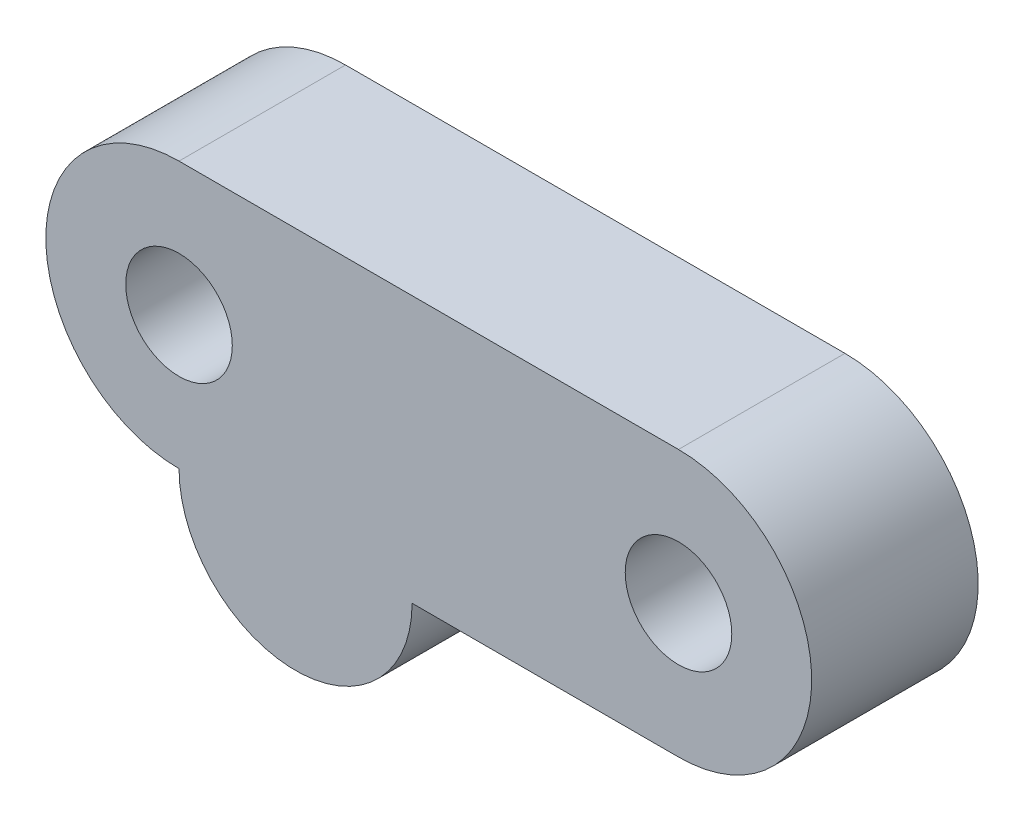
SolidWorks part; units mm, degrees
material "ABS"
ref_plane "Front Plane" through (0, 0, 0) normal (0, 0, 1) x (1, 0, 0)
ref_plane "Top Plane" through (0, 0, 0) normal (0, 1, 0) x (1, 0, 0)
ref_plane "Right Plane" through (0, 0, 0) normal (1, 0, 0) x (0, 0, -1)
sketch "Sketch1" plane through (0, 0, 0) normal (0, 0, 1) x (1, 0, 0)
  line L0 (0, 0) -> (15, 0) construction
  line L1 (0, 4) -> (15, 4)
  line L3 (7, -4) -> (15, -4)
  line L4 (0, -4) -> (7, -4) construction
  line L5 (0, 0) -> (15, 0) construction
  arc A0 (0, 4) -> (0, -4) centre (0, 0) ccw
  arc A1 (15, -4) -> (15, 4) centre (15, 0) ccw
  circle A2 centre (0, 0) radius 1.6
  circle A3 centre (15, 0) radius 1.6
  arc A4 (0, -4) -> (7, -4) centre (3.5, -4) ccw
extrude "Boss-Extrude1" add sketch "Sketch1" along normal blind 5
sketch "Sketch2" plane through (0, 0, 0) normal (0, 0, -1) x (-1, 0, 0)
  line L1 (3.4641, 0) -> (1.7321, 3)
  line L2 (1.7321, 3) -> (-1.7321, 3)
  line L3 (-1.7321, 3) -> (-3.4641, 0)
  line L4 (-3.4641, 0) -> (-1.7321, -3)
  line L5 (-1.7321, -3) -> (1.7321, -3)
  line L6 (1.7321, -3) -> (3.4641, 0)
  line L7 (-11.5359, 0) -> (-13.2679, 3)
  line L8 (-13.2679, 3) -> (-16.7321, 3)
  line L9 (-16.7321, 3) -> (-18.4641, 0)
  line L10 (-18.4641, 0) -> (-16.7321, -3)
  line L11 (-16.7321, -3) -> (-13.2679, -3)
  line L12 (-13.2679, -3) -> (-11.5359, 0)
  circle A2 centre (0, 0) radius 3 construction
  circle A3 centre (-15, 0) radius 3 construction
  dimension "D1" = 6
  dimension "D2" = 6
extrude "Cut-Extrude1" cut sketch "Sketch2" against normal blind 2
